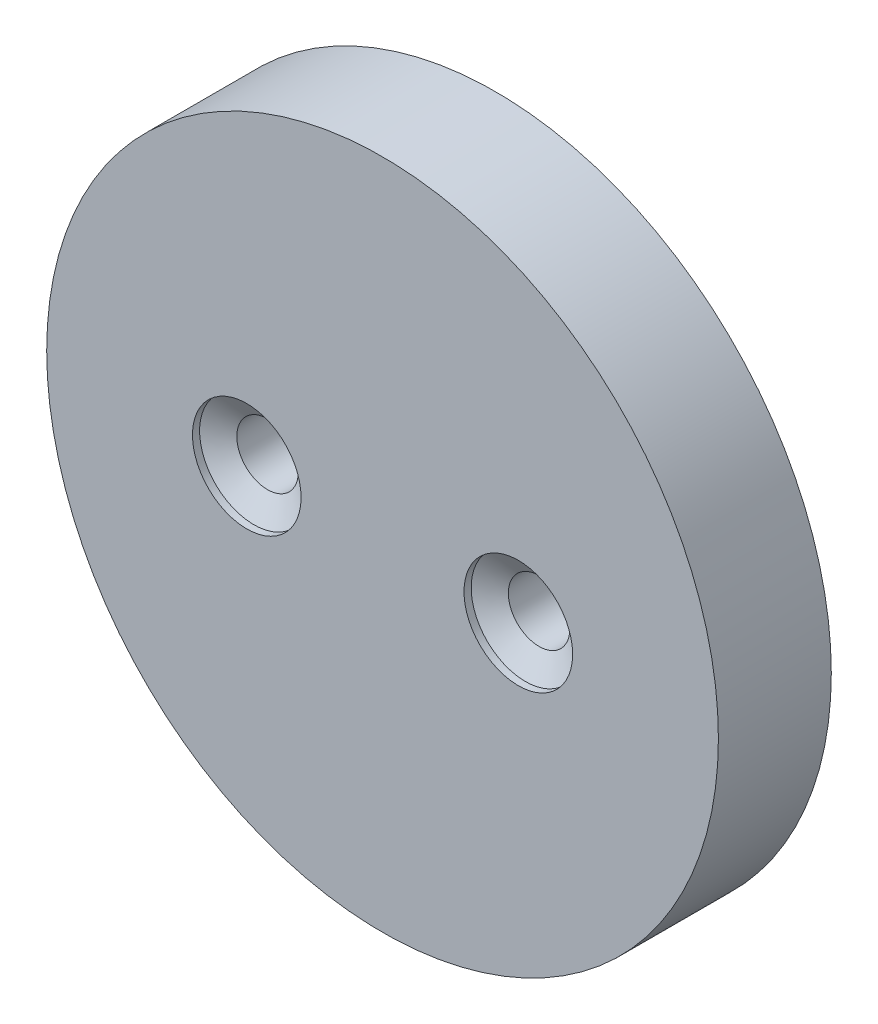
SolidWorks part; units mm, degrees
ref_plane "Front Plane" through (0, 0, 0) normal (0, 0, 1) x (1, 0, 0)
ref_plane "Top Plane" through (0, 0, 0) normal (0, 1, 0) x (1, 0, 0)
ref_plane "Right Plane" through (0, 0, 0) normal (1, 0, 0) x (0, 0, -1)
sketch "Sketch1" plane through (0, 0, 0) normal (0, 0, 1) x (1, 0, 0)
  circle A0 centre (0, 0) radius 23.5
  dimension "D1" = 47
extrude "Boss-Extrude1" add sketch "Sketch1" along normal blind 7.9
sketch "Sketch2" plane through (0, 0, 7.9) normal (0, 0, 1) x (1, 0, 0)
  line L0 (-9.5, 0) -> (9.5, 0)
  circle A0 centre (-9.5, 0) radius 2.15
  circle A1 centre (9.5, 0) radius 2.15
  point P0 (9.5813, 0)
  point P4 (-17.7032, 0)
  point P5 (0, 0)
  point P8 (0, 0)
  dimension "D1" = 4.3
  dimension "D2" = 19
extrude "Cut-Extrude1" cut sketch "Sketch2" against normal up to next
sketch "Sketch3" plane through (0, 0, 7.9) normal (0, 0, 1) x (1, 0, 0)
  circle A4 centre (-9.5, 0) radius 3.8
  circle A5 centre (9.5, 0) radius 3.8
  dimension "D1" = 7.6
extrude "Cut-Extrude2" cut sketch "Sketch3" against normal blind 0.5
sketch "Sketch6" plane through (0, 0, 0) normal (0, 1, 0) x (1, 0, 0)
  line L4 (-13.3, -7.4) -> (-5.7, -7.4) construction
  line L5 (-13.3, -7.4) -> (-9.5, -7.4)
  line L6 (-9.5, -7.4) -> (-9.5, -5.2061)
  line L7 (-9.5, -5.2061) -> (-13.3, -7.4)
  dimension "D1" = 30
sketch "Sketch7" plane through (0, 0, 0) normal (0, 1, 0) x (1, 0, 0)
  line L0 (5.7, -7.4) -> (13.3, -7.4) construction
  line L1 (5.7, -7.4) -> (9.5, -7.4)
  line L2 (9.5, -7.4) -> (9.5, -5.2061)
  line L3 (9.5, -5.2061) -> (5.7, -7.4)
  dimension "D1" = 30
revolve "Cut-Revolve5" cut sketch "Sketch7" angle 360 about L2
revolve "Cut-Revolve6" cut sketch "Sketch6" angle 360 about L6
